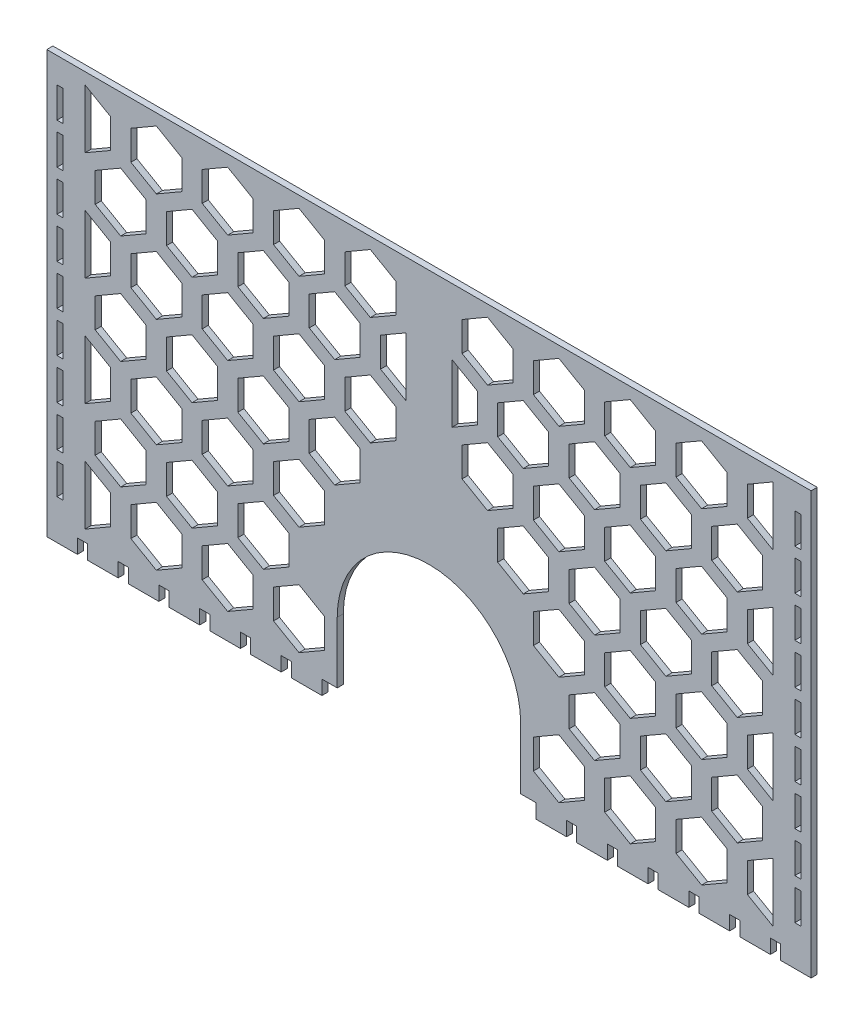
SolidWorks part; units mm, degrees
material "Brass"
ref_plane "Front Plane" through (0, 0, 0) normal (0, 0, 1) x (1, 0, 0)
ref_plane "Top Plane" through (0, 0, 0) normal (0, 1, 0) x (1, 0, 0)
ref_plane "Right Plane" through (0, 0, 0) normal (1, 0, 0) x (0, 0, -1)
sketch "Sketch1" plane through (0, 0, 0) normal (0, 0, 1) x (1, 0, 0)
  line L0 (0, 100) -> (0, -100) construction
  line L2 (-187.5, -100) -> (-187.5, 100)
  line L3 (-187.5, 100) -> (187.5, 100)
  line L4 (187.5, -100) -> (187.5, 100)
  line L6 (-187.5, 0) -> (187.5, 0) construction
  line L11 (-187.5, -100) -> (187.5, -100)
  line L13 (-187.5, 0) -> (-182.5, 0) construction
  line L15 (-45, -70) -> (-45, -100)
  line L16 (-45, -100) -> (45, -100)
  line L17 (45, -70) -> (45, -100)
  line L18 (-179.5, 7.5) -> (-182.5, 7.5)
  line L19 (-179.5, 7.5) -> (-179.5, -7.5)
  line L20 (-179.5, -7.5) -> (-182.5, -7.5)
  line L21 (-182.5, 7.5) -> (-182.5, -7.5)
  line L22 (-179.5, 27.5) -> (-179.5, 12.5)
  line L23 (-179.5, 27.5) -> (-182.5, 27.5)
  line L24 (-182.5, 27.5) -> (-182.5, 12.5)
  line L25 (-179.5, 12.5) -> (-182.5, 12.5)
  line L26 (-179.5, 47.5) -> (-179.5, 32.5)
  line L27 (-179.5, 47.5) -> (-182.5, 47.5)
  line L28 (-182.5, 47.5) -> (-182.5, 32.5)
  line L29 (-179.5, 32.5) -> (-182.5, 32.5)
  line L30 (-179.5, 67.5) -> (-179.5, 52.5)
  line L31 (-179.5, 67.5) -> (-182.5, 67.5)
  line L32 (-182.5, 67.5) -> (-182.5, 52.5)
  line L33 (-179.5, 52.5) -> (-182.5, 52.5)
  line L34 (-179.5, 87.5) -> (-179.5, 72.5)
  line L35 (-179.5, 87.5) -> (-182.5, 87.5)
  line L36 (-182.5, 87.5) -> (-182.5, 72.5)
  line L37 (-179.5, 72.5) -> (-182.5, 72.5)
  line L38 (-179.5, 7.5) -> (-179.5, -7.5)
  line L39 (-179.5, 7.5) -> (-182.5, 7.5)
  line L40 (-182.5, 7.5) -> (-182.5, -7.5)
  line L41 (-179.5, -7.5) -> (-182.5, -7.5)
  line L42 (-179.5, 27.5) -> (-179.5, 12.5)
  line L43 (-179.5, 27.5) -> (-182.5, 27.5)
  line L44 (-182.5, 27.5) -> (-182.5, 12.5)
  line L45 (-179.5, 12.5) -> (-182.5, 12.5)
  line L46 (-179.5, 47.5) -> (-179.5, 32.5)
  line L47 (-179.5, 47.5) -> (-182.5, 47.5)
  line L48 (-182.5, 47.5) -> (-182.5, 32.5)
  line L49 (-179.5, 32.5) -> (-182.5, 32.5)
  line L50 (-179.5, 67.5) -> (-179.5, 52.5)
  line L51 (-179.5, 67.5) -> (-182.5, 67.5)
  line L52 (-182.5, 67.5) -> (-182.5, 52.5)
  line L53 (-179.5, 52.5) -> (-182.5, 52.5)
  line L54 (-179.5, -12.5) -> (-179.5, -27.5)
  line L55 (-179.5, -12.5) -> (-182.5, -12.5)
  line L56 (-182.5, -12.5) -> (-182.5, -27.5)
  line L57 (-179.5, -27.5) -> (-182.5, -27.5)
  line L58 (-179.5, 7.5) -> (-179.5, -7.5)
  line L59 (-179.5, 7.5) -> (-182.5, 7.5)
  line L60 (-182.5, 7.5) -> (-182.5, -7.5)
  line L61 (-179.5, -7.5) -> (-182.5, -7.5)
  line L62 (-179.5, 27.5) -> (-179.5, 12.5)
  line L63 (-179.5, 27.5) -> (-182.5, 27.5)
  line L64 (-182.5, 27.5) -> (-182.5, 12.5)
  line L65 (-179.5, 12.5) -> (-182.5, 12.5)
  line L66 (-179.5, 47.5) -> (-179.5, 32.5)
  line L67 (-179.5, 47.5) -> (-182.5, 47.5)
  line L68 (-182.5, 47.5) -> (-182.5, 32.5)
  line L69 (-179.5, 32.5) -> (-182.5, 32.5)
  line L70 (-179.5, -32.5) -> (-179.5, -47.5)
  line L71 (-179.5, -32.5) -> (-182.5, -32.5)
  line L72 (-182.5, -32.5) -> (-182.5, -47.5)
  line L73 (-179.5, -47.5) -> (-182.5, -47.5)
  line L74 (-179.5, -12.5) -> (-179.5, -27.5)
  line L75 (-179.5, -12.5) -> (-182.5, -12.5)
  line L76 (-182.5, -12.5) -> (-182.5, -27.5)
  line L77 (-179.5, -27.5) -> (-182.5, -27.5)
  line L78 (-179.5, 7.5) -> (-179.5, -7.5)
  line L79 (-179.5, 7.5) -> (-182.5, 7.5)
  line L80 (-182.5, 7.5) -> (-182.5, -7.5)
  line L81 (-179.5, -7.5) -> (-182.5, -7.5)
  line L82 (-179.5, 27.5) -> (-179.5, 12.5)
  line L83 (-179.5, 27.5) -> (-182.5, 27.5)
  line L84 (-182.5, 27.5) -> (-182.5, 12.5)
  line L85 (-179.5, 12.5) -> (-182.5, 12.5)
  line L86 (-179.5, -52.5) -> (-179.5, -67.5)
  line L87 (-179.5, -52.5) -> (-182.5, -52.5)
  line L88 (-182.5, -52.5) -> (-182.5, -67.5)
  line L89 (-179.5, -67.5) -> (-182.5, -67.5)
  line L90 (-179.5, -32.5) -> (-179.5, -47.5)
  line L91 (-179.5, -32.5) -> (-182.5, -32.5)
  line L92 (-182.5, -32.5) -> (-182.5, -47.5)
  line L93 (-179.5, -47.5) -> (-182.5, -47.5)
  line L94 (-179.5, -12.5) -> (-179.5, -27.5)
  line L95 (-179.5, -12.5) -> (-182.5, -12.5)
  line L96 (-182.5, -12.5) -> (-182.5, -27.5)
  line L97 (-179.5, -27.5) -> (-182.5, -27.5)
  line L98 (-179.5, 7.5) -> (-179.5, -7.5)
  line L99 (-179.5, 7.5) -> (-182.5, 7.5)
  line L100 (-182.5, 7.5) -> (-182.5, -7.5)
  line L101 (-179.5, -7.5) -> (-182.5, -7.5)
  line L102 (-179.5, -12.5) -> (-179.5, -27.5)
  line L103 (-179.5, -12.5) -> (-182.5, -12.5)
  line L104 (-182.5, -12.5) -> (-182.5, -27.5)
  line L105 (-179.5, -27.5) -> (-182.5, -27.5)
  line L106 (-179.5, -32.5) -> (-179.5, -47.5)
  line L107 (-179.5, -32.5) -> (-182.5, -32.5)
  line L108 (-182.5, -32.5) -> (-182.5, -47.5)
  line L109 (-179.5, -47.5) -> (-182.5, -47.5)
  line L110 (-179.5, -52.5) -> (-179.5, -67.5)
  line L111 (-179.5, -52.5) -> (-182.5, -52.5)
  line L112 (-182.5, -52.5) -> (-182.5, -67.5)
  line L113 (-179.5, -67.5) -> (-182.5, -67.5)
  line L114 (-179.5, -72.5) -> (-179.5, -87.5)
  line L115 (-179.5, -72.5) -> (-182.5, -72.5)
  line L116 (-182.5, -72.5) -> (-182.5, -87.5)
  line L117 (-179.5, -87.5) -> (-182.5, -87.5)
  line L118 (187.5, 0) -> (182.5, 0) construction
  line L119 (182.5, 27.5) -> (179.5, 27.5)
  line L120 (179.5, 27.5) -> (179.5, 12.5)
  line L121 (182.5, 7.5) -> (179.5, 7.5)
  line L122 (182.5, 7.5) -> (182.5, -7.5)
  line L123 (182.5, -7.5) -> (179.5, -7.5)
  line L124 (179.5, 7.5) -> (179.5, -7.5)
  line L221 (182.5, 12.5) -> (179.5, 12.5)
  line L222 (182.5, 27.5) -> (182.5, 12.5)
  line L223 (182.5, 47.5) -> (179.5, 47.5)
  line L224 (179.5, 47.5) -> (179.5, 32.5)
  line L225 (182.5, 32.5) -> (179.5, 32.5)
  line L226 (182.5, 47.5) -> (182.5, 32.5)
  line L227 (182.5, 67.5) -> (179.5, 67.5)
  line L228 (179.5, 67.5) -> (179.5, 52.5)
  line L229 (182.5, 52.5) -> (179.5, 52.5)
  line L230 (182.5, 67.5) -> (182.5, 52.5)
  line L231 (182.5, 87.5) -> (179.5, 87.5)
  line L232 (179.5, 87.5) -> (179.5, 72.5)
  line L233 (182.5, 72.5) -> (179.5, 72.5)
  line L234 (182.5, 87.5) -> (182.5, 72.5)
  line L235 (182.5, -12.5) -> (179.5, -12.5)
  line L236 (179.5, -12.5) -> (179.5, -27.5)
  line L237 (182.5, -27.5) -> (179.5, -27.5)
  line L238 (182.5, -12.5) -> (182.5, -27.5)
  line L239 (182.5, -32.5) -> (179.5, -32.5)
  line L240 (179.5, -32.5) -> (179.5, -47.5)
  line L241 (182.5, -47.5) -> (179.5, -47.5)
  line L242 (182.5, -32.5) -> (182.5, -47.5)
  line L243 (182.5, -52.5) -> (179.5, -52.5)
  line L244 (179.5, -52.5) -> (179.5, -67.5)
  line L245 (182.5, -67.5) -> (179.5, -67.5)
  line L246 (182.5, -52.5) -> (182.5, -67.5)
  line L247 (182.5, -72.5) -> (179.5, -72.5)
  line L248 (179.5, -72.5) -> (179.5, -87.5)
  line L249 (182.5, -87.5) -> (179.5, -87.5)
  line L250 (182.5, -72.5) -> (182.5, -87.5)
  arc A1 (45, -70) -> (-45, -70) centre (0, -70) ccw
  circle A2 centre (0, -70) radius 40 construction
  point P0 (0, 0)
  point P16 (0, 0)
  point P17 (-182.5, 0)
  point P121 (182.5, 0)
  point P122 (181, 7.5)
  dimension "D3" = 90
  dimension "D5" = 30
  dimension "D4" = 142.5
  dimension "D6" = 80
  dimension "D2" = 187.5
  dimension "D7" = 15
  dimension "D8" = 3
  dimension "D9" = 5
  dimension "D12" = 5
  dimension "D13" = 5
  dimension "D14" = 200
  dimension "D15" = 15
  dimension "D16" = 3
  dimension "D17" = 5
  dimension "D18" = 5
  dimension "D19" = 5
  dimension "D21" = 5
  dimension "D10" = 5
  dimension "D11" = 5
  dimension "D20" = 5
extrude "Boss-Extrude1" add sketch "Sketch1" along normal blind 3 contours A1 L17 L11 L4 L3 L2 L15
sketch "Sketch7" plane through (0, -100, 0) normal (0, -1, 0) x (1, 0, 0)
  line L0 (-187.5, 0) -> (-45, 0) construction
  line L1 (-187.5, 3) -> (-172.5, 3)
  line L2 (-187.5, 3) -> (-187.5, 0)
  line L3 (-187.5, 0) -> (-172.5, 0)
  line L4 (-172.5, 3) -> (-172.5, 0)
  line L5 (-167.5, 3) -> (-167.5, 0)
  line L6 (-167.5, 3) -> (-152.5, 3)
  line L7 (-152.5, 3) -> (-152.5, 0)
  line L8 (-167.5, 0) -> (-152.5, 0)
  line L9 (-147.5, 3) -> (-147.5, 0)
  line L10 (-147.5, 3) -> (-132.5, 3)
  line L11 (-132.5, 3) -> (-132.5, 0)
  line L12 (-147.5, 0) -> (-132.5, 0)
  line L13 (-127.5, 3) -> (-127.5, 0)
  line L14 (-127.5, 3) -> (-112.5, 3)
  line L15 (-112.5, 3) -> (-112.5, 0)
  line L16 (-127.5, 0) -> (-112.5, 0)
  line L17 (-107.5, 3) -> (-107.5, 0)
  line L18 (-107.5, 3) -> (-92.5, 3)
  line L19 (-92.5, 3) -> (-92.5, 0)
  line L20 (-107.5, 0) -> (-92.5, 0)
  line L21 (-87.5, 3) -> (-87.5, 0)
  line L22 (-87.5, 3) -> (-72.5, 3)
  line L23 (-72.5, 3) -> (-72.5, 0)
  line L24 (-87.5, 0) -> (-72.5, 0)
  line L25 (-67.5, 3) -> (-67.5, 0)
  line L26 (-67.5, 3) -> (-52.5, 3)
  line L27 (-52.5, 3) -> (-52.5, 0)
  line L28 (-67.5, 0) -> (-52.5, 0)
  dimension "D1" = 15
  dimension "D3" = 5
  dimension "D2" = 7
extrude "Boss-Extrude2" add sketch "Sketch7" along normal blind 7
sketch "Sketch8" plane through (0, -100, 0) normal (0, -1, 0) x (1, 0, 0)
  line L0 (45, 3) -> (187.5, 3) construction
  line L1 (187.5, 0) -> (172.5, 0)
  line L2 (187.5, 0) -> (187.5, 3)
  line L3 (187.5, 3) -> (172.5, 3)
  line L4 (172.5, 0) -> (172.5, 3)
  line L5 (167.5, 0) -> (167.5, 3)
  line L6 (167.5, 0) -> (152.5, 0)
  line L7 (152.5, 0) -> (152.5, 3)
  line L8 (167.5, 3) -> (152.5, 3)
  line L9 (147.5, 0) -> (147.5, 3)
  line L10 (147.5, 0) -> (132.5, 0)
  line L11 (132.5, 0) -> (132.5, 3)
  line L12 (147.5, 3) -> (132.5, 3)
  line L13 (127.5, 0) -> (127.5, 3)
  line L14 (127.5, 0) -> (112.5, 0)
  line L15 (112.5, 0) -> (112.5, 3)
  line L16 (127.5, 3) -> (112.5, 3)
  line L17 (107.5, 0) -> (107.5, 3)
  line L18 (107.5, 0) -> (92.5, 0)
  line L19 (92.5, 0) -> (92.5, 3)
  line L20 (107.5, 3) -> (92.5, 3)
  line L21 (87.5, 0) -> (87.5, 3)
  line L22 (87.5, 0) -> (72.5, 0)
  line L23 (72.5, 0) -> (72.5, 3)
  line L24 (87.5, 3) -> (72.5, 3)
  line L25 (67.5, 0) -> (67.5, 3)
  line L26 (67.5, 0) -> (52.5, 0)
  line L27 (52.5, 0) -> (52.5, 3)
  line L28 (67.5, 3) -> (52.5, 3)
  dimension "D1" = 15
  dimension "D3" = 5
  dimension "D2" = 7
extrude "Boss-Extrude3" add sketch "Sketch8" along normal blind 7
sketch "Sketch10" plane through (0, 0, 0) normal (0, 0, -1) x (-1, 0, 0)
  line L0 (-45, -100) -> (-45, 100) construction
  line L1 (187.5, 100) -> (-187.5, 100) construction
  line L2 (-45, 100) -> (-187.5, 100) construction
  line L3 (-187.5, 100) -> (-187.5, -100) construction
  line L4 (-187.5, -107) -> (-187.5, 100) construction
  line L5 (-187.5, -100) -> (-45, -100) construction
  line L6 (-116.25, 100) -> (-116.25, -100) construction
  line L7 (-98.75, -26.6506) -> (-98.75, -100) construction
  line L8 (-45, 0) -> (-187.5, 0) construction
  line L9 (-116.25, -14.4338) -> (-103.75, -7.2169)
  line L10 (-103.75, -7.2169) -> (-103.75, 7.2169)
  line L11 (-103.75, 7.2169) -> (-116.25, 14.4338)
  line L12 (-116.25, 14.4338) -> (-128.75, 7.2169)
  line L13 (-128.75, 7.2169) -> (-128.75, -7.2169)
  line L14 (-128.75, -7.2169) -> (-116.25, -14.4338)
  line L15 (-98.75, -100) -> (-98.75, 100) construction
  line L16 (-98.75, -12.2169) -> (-111.25, -19.4338)
  line L17 (-111.25, -19.4338) -> (-111.25, -33.8675)
  line L18 (-111.25, -33.8675) -> (-98.75, -41.0844)
  line L19 (-98.75, -41.0844) -> (-86.25, -33.8675)
  line L20 (-86.25, -33.8675) -> (-86.25, -19.4338)
  line L21 (-86.25, -19.4338) -> (-98.75, -12.2169)
  line L22 (-133.75, -100) -> (-133.75, 100) construction
  line L23 (-45, -26.6506) -> (-187.5, -26.6506) construction
  line L24 (-133.75, -41.0844) -> (-121.25, -33.8675)
  line L25 (-121.25, -33.8675) -> (-121.25, -19.4338)
  line L26 (-121.25, -19.4338) -> (-133.75, -12.2169)
  line L27 (-133.75, -12.2169) -> (-146.25, -19.4338)
  line L28 (-146.25, -19.4338) -> (-146.25, -33.8675)
  line L29 (-146.25, -33.8675) -> (-133.75, -41.0844)
  line L36 (187.5, -107) -> (187.5, 100) construction
  line L37 (-116.25, -67.735) -> (-103.75, -60.5181)
  line L38 (-103.75, -60.5181) -> (-103.75, -46.0844)
  line L39 (-103.75, -46.0844) -> (-116.25, -38.8675)
  line L40 (-116.25, -38.8675) -> (-128.75, -46.0844)
  line L41 (-128.75, -46.0844) -> (-128.75, -60.5181)
  line L42 (-128.75, -60.5181) -> (-116.25, -67.735)
  line L61 (-81.25, -14.4338) -> (-68.75, -7.2169)
  line L62 (-68.75, -7.2169) -> (-68.75, 7.2169)
  line L63 (-68.75, 7.2169) -> (-81.25, 14.4338)
  line L64 (-81.25, 14.4338) -> (-93.75, 7.2169)
  line L65 (-93.75, 7.2169) -> (-93.75, -7.2169)
  line L66 (-93.75, -7.2169) -> (-81.25, -14.4338)
  line L67 (-81.25, -67.735) -> (-68.75, -60.5181)
  line L68 (-68.75, -60.5181) -> (-68.75, -46.0844)
  line L69 (-68.75, -46.0844) -> (-81.25, -38.8675)
  line L70 (-81.25, -38.8675) -> (-93.75, -46.0844)
  line L71 (-93.75, -46.0844) -> (-93.75, -60.5181)
  line L72 (-93.75, -60.5181) -> (-81.25, -67.735)
  line L73 (-63.75, -41.0844) -> (-51.25, -33.8675)
  line L74 (-51.25, -33.8675) -> (-51.25, -19.4338)
  line L75 (-51.25, -19.4338) -> (-63.75, -12.2169)
  line L76 (-63.75, -12.2169) -> (-76.25, -19.4338)
  line L77 (-76.25, -19.4338) -> (-76.25, -33.8675)
  line L78 (-76.25, -33.8675) -> (-63.75, -41.0844)
  line L79 (-151.25, -14.4338) -> (-138.75, -7.2169)
  line L80 (-138.75, -7.2169) -> (-138.75, 7.2169)
  line L81 (-138.75, 7.2169) -> (-151.25, 14.4338)
  line L82 (-151.25, 14.4338) -> (-163.75, 7.2169)
  line L83 (-163.75, 7.2169) -> (-163.75, -7.2169)
  line L84 (-163.75, -7.2169) -> (-151.25, -14.4338)
  line L85 (-151.25, -67.735) -> (-138.75, -60.5181)
  line L86 (-138.75, -60.5181) -> (-138.75, -46.0844)
  line L87 (-138.75, -46.0844) -> (-151.25, -38.8675)
  line L88 (-151.25, -38.8675) -> (-163.75, -46.0844)
  line L89 (-163.75, -46.0844) -> (-163.75, -60.5181)
  line L90 (-163.75, -60.5181) -> (-151.25, -67.735)
  line L91 (-168.75, -41.0844) -> (-156.25, -33.8675)
  line L92 (-156.25, -33.8675) -> (-156.25, -19.4338)
  line L93 (-156.25, -19.4338) -> (-168.75, -12.2169)
  line L96 (-168.75, -12.2169) -> (-168.75, -41.0844)
  line L103 (-133.75, 12.2169) -> (-121.25, 19.4338)
  line L104 (-121.25, 19.4338) -> (-121.25, 33.8675)
  line L105 (-121.25, 33.8675) -> (-133.75, 41.0844)
  line L106 (-133.75, 41.0844) -> (-146.25, 33.8675)
  line L107 (-146.25, 33.8675) -> (-146.25, 19.4338)
  line L108 (-146.25, 19.4338) -> (-133.75, 12.2169)
  line L109 (-98.75, 12.2169) -> (-86.25, 19.4338)
  line L110 (-86.25, 19.4338) -> (-86.25, 33.8675)
  line L111 (-86.25, 33.8675) -> (-98.75, 41.0844)
  line L112 (-98.75, 41.0844) -> (-111.25, 33.8675)
  line L113 (-111.25, 33.8675) -> (-111.25, 19.4338)
  line L114 (-111.25, 19.4338) -> (-98.75, 12.2169)
  line L115 (-168.75, 12.2169) -> (-156.25, 19.4338)
  line L116 (-156.25, 19.4338) -> (-156.25, 33.8675)
  line L117 (-156.25, 33.8675) -> (-168.75, 41.0844)
  line L118 (-168.75, 41.0844) -> (-168.75, 12.2169)
  line L119 (-63.75, 12.2169) -> (-51.25, 19.4338)
  line L120 (-51.25, 19.4338) -> (-51.25, 33.8675)
  line L121 (-51.25, 33.8675) -> (-63.75, 41.0844)
  line L122 (-63.75, 41.0844) -> (-76.25, 33.8675)
  line L123 (-76.25, 33.8675) -> (-76.25, 19.4338)
  line L124 (-76.25, 19.4338) -> (-63.75, 12.2169)
  line L125 (-28.75, 12.2169) -> (-16.25, 19.4338)
  line L126 (-16.25, 19.4338) -> (-16.25, 33.8675)
  line L127 (-16.25, 33.8675) -> (-28.75, 41.0844)
  line L128 (-28.75, 41.0844) -> (-41.25, 33.8675)
  line L129 (-41.25, 33.8675) -> (-41.25, 19.4338)
  line L130 (-41.25, 19.4338) -> (-28.75, 12.2169)
  line L131 (-46.25, -14.4338) -> (-33.75, -7.2169)
  line L132 (-33.75, -7.2169) -> (-33.75, 7.2169)
  line L133 (-33.75, 7.2169) -> (-46.25, 14.4338)
  line L134 (-46.25, 14.4338) -> (-58.75, 7.2169)
  line L135 (-58.75, 7.2169) -> (-58.75, -7.2169)
  line L136 (-58.75, -7.2169) -> (-46.25, -14.4338)
  line L137 (0, -25) -> (0, 100) construction
  line L138 (-133.75, -94.3857) -> (-121.25, -87.1688)
  line L139 (-121.25, -87.1688) -> (-121.25, -72.735)
  line L140 (-121.25, -72.735) -> (-133.75, -65.5181)
  line L141 (-133.75, -65.5181) -> (-146.25, -72.735)
  line L142 (-146.25, -72.735) -> (-146.25, -87.1688)
  line L143 (-146.25, -87.1688) -> (-133.75, -94.3857)
  line L144 (-98.75, -94.3857) -> (-86.25, -87.1688)
  line L145 (-86.25, -87.1688) -> (-86.25, -72.735)
  line L146 (-86.25, -72.735) -> (-98.75, -65.5181)
  line L147 (-98.75, -65.5181) -> (-111.25, -72.735)
  line L148 (-111.25, -72.735) -> (-111.25, -87.1688)
  line L149 (-111.25, -87.1688) -> (-98.75, -94.3857)
  line L150 (-63.75, -94.3857) -> (-51.25, -87.1688)
  line L151 (-51.25, -87.1688) -> (-51.25, -72.735)
  line L152 (-51.25, -72.735) -> (-63.75, -65.5181)
  line L153 (-63.75, -65.5181) -> (-76.25, -72.735)
  line L154 (-76.25, -72.735) -> (-76.25, -87.1688)
  line L155 (-76.25, -87.1688) -> (-63.75, -94.3857)
  line L156 (-168.75, -94.3857) -> (-156.25, -87.1688)
  line L157 (-156.25, -87.1688) -> (-156.25, -72.735)
  line L158 (-156.25, -72.735) -> (-168.75, -65.5181)
  line L159 (-168.75, -65.5181) -> (-168.75, -94.3857)
  line L160 (-151.25, 38.8675) -> (-138.75, 46.0844)
  line L161 (-138.75, 46.0844) -> (-138.75, 60.5181)
  line L162 (-138.75, 60.5181) -> (-151.25, 67.735)
  line L163 (-151.25, 67.735) -> (-163.75, 60.5181)
  line L164 (-163.75, 60.5181) -> (-163.75, 46.0844)
  line L165 (-163.75, 46.0844) -> (-151.25, 38.8675)
  line L166 (-116.25, 38.8675) -> (-103.75, 46.0844)
  line L167 (-103.75, 46.0844) -> (-103.75, 60.5181)
  line L168 (-103.75, 60.5181) -> (-116.25, 67.735)
  line L169 (-116.25, 67.735) -> (-128.75, 60.5181)
  line L170 (-128.75, 60.5181) -> (-128.75, 46.0844)
  line L171 (-128.75, 46.0844) -> (-116.25, 38.8675)
  line L172 (-81.25, 38.8675) -> (-68.75, 46.0844)
  line L173 (-68.75, 46.0844) -> (-68.75, 60.5181)
  line L174 (-68.75, 60.5181) -> (-81.25, 67.735)
  line L175 (-81.25, 67.735) -> (-93.75, 60.5181)
  line L176 (-93.75, 60.5181) -> (-93.75, 46.0844)
  line L177 (-93.75, 46.0844) -> (-81.25, 38.8675)
  line L178 (-46.25, 38.8675) -> (-33.75, 46.0844)
  line L179 (-33.75, 46.0844) -> (-33.75, 60.5181)
  line L180 (-33.75, 60.5181) -> (-46.25, 67.735)
  line L181 (-46.25, 67.735) -> (-58.75, 60.5181)
  line L182 (-58.75, 60.5181) -> (-58.75, 46.0844)
  line L183 (-58.75, 46.0844) -> (-46.25, 38.8675)
  line L187 (-11.25, 67.735) -> (-23.75, 60.5181)
  line L188 (-23.75, 60.5181) -> (-23.75, 46.0844)
  line L189 (-23.75, 46.0844) -> (-11.25, 38.8675)
  line L190 (-11.25, 67.735) -> (-11.25, 38.8675)
  line L191 (-133.75, 65.5181) -> (-121.25, 72.735)
  line L192 (-121.25, 72.735) -> (-121.25, 87.1688)
  line L193 (-121.25, 87.1688) -> (-133.75, 94.3857)
  line L194 (-133.75, 94.3857) -> (-146.25, 87.1688)
  line L195 (-146.25, 87.1688) -> (-146.25, 72.735)
  line L196 (-146.25, 72.735) -> (-133.75, 65.5181)
  line L197 (-98.75, 65.5181) -> (-86.25, 72.735)
  line L198 (-86.25, 72.735) -> (-86.25, 87.1688)
  line L199 (-86.25, 87.1688) -> (-98.75, 94.3857)
  line L200 (-98.75, 94.3857) -> (-111.25, 87.1688)
  line L201 (-111.25, 87.1688) -> (-111.25, 72.735)
  line L202 (-111.25, 72.735) -> (-98.75, 65.5181)
  line L203 (-168.75, 65.5181) -> (-156.25, 72.735)
  line L204 (-156.25, 72.735) -> (-156.25, 87.1688)
  line L205 (-156.25, 87.1688) -> (-168.75, 94.3857)
  line L206 (-168.75, 94.3857) -> (-168.75, 65.5181)
  line L207 (-63.75, 65.5181) -> (-51.25, 72.735)
  line L208 (-51.25, 72.735) -> (-51.25, 87.1688)
  line L209 (-51.25, 87.1688) -> (-63.75, 94.3857)
  line L210 (-63.75, 94.3857) -> (-76.25, 87.1688)
  line L211 (-76.25, 87.1688) -> (-76.25, 72.735)
  line L212 (-76.25, 72.735) -> (-63.75, 65.5181)
  line L213 (-28.75, 65.5181) -> (-16.25, 72.735)
  line L214 (-16.25, 72.735) -> (-16.25, 87.1688)
  line L215 (-16.25, 87.1688) -> (-28.75, 94.3857)
  line L216 (-28.75, 94.3857) -> (-41.25, 87.1688)
  line L217 (-41.25, 87.1688) -> (-41.25, 72.735)
  line L218 (-41.25, 72.735) -> (-28.75, 65.5181)
  line L219 (45, -26.6506) -> (187.5, -26.6506) construction
  line L220 (133.75, -100) -> (133.75, 100) construction
  line L221 (98.75, -100) -> (98.75, 100) construction
  line L222 (45, 0) -> (187.5, 0) construction
  line L223 (98.75, -26.6506) -> (98.75, -100) construction
  line L224 (116.25, 100) -> (116.25, -100) construction
  line L225 (187.5, -100) -> (45, -100) construction
  line L226 (187.5, 100) -> (187.5, -100) construction
  line L227 (45, 100) -> (187.5, 100) construction
  line L228 (45, -100) -> (45, 100) construction
  line L229 (41.25, 72.735) -> (28.75, 65.5181)
  line L230 (41.25, 87.1688) -> (41.25, 72.735)
  line L231 (28.75, 94.3857) -> (41.25, 87.1688)
  line L232 (16.25, 87.1688) -> (28.75, 94.3857)
  line L233 (16.25, 72.735) -> (16.25, 87.1688)
  line L234 (28.75, 65.5181) -> (16.25, 72.735)
  line L235 (76.25, 72.735) -> (63.75, 65.5181)
  line L236 (76.25, 87.1688) -> (76.25, 72.735)
  line L237 (63.75, 94.3857) -> (76.25, 87.1688)
  line L238 (51.25, 87.1688) -> (63.75, 94.3857)
  line L239 (51.25, 72.735) -> (51.25, 87.1688)
  line L240 (63.75, 65.5181) -> (51.25, 72.735)
  line L241 (168.75, 94.3857) -> (168.75, 65.5181)
  line L242 (156.25, 87.1688) -> (168.75, 94.3857)
  line L243 (156.25, 72.735) -> (156.25, 87.1688)
  line L244 (168.75, 65.5181) -> (156.25, 72.735)
  line L245 (111.25, 72.735) -> (98.75, 65.5181)
  line L246 (111.25, 87.1688) -> (111.25, 72.735)
  line L247 (98.75, 94.3857) -> (111.25, 87.1688)
  line L248 (86.25, 87.1688) -> (98.75, 94.3857)
  line L249 (86.25, 72.735) -> (86.25, 87.1688)
  line L250 (98.75, 65.5181) -> (86.25, 72.735)
  line L251 (146.25, 72.735) -> (133.75, 65.5181)
  line L252 (146.25, 87.1688) -> (146.25, 72.735)
  line L253 (133.75, 94.3857) -> (146.25, 87.1688)
  line L254 (121.25, 87.1688) -> (133.75, 94.3857)
  line L255 (121.25, 72.735) -> (121.25, 87.1688)
  line L256 (133.75, 65.5181) -> (121.25, 72.735)
  line L257 (11.25, 67.735) -> (11.25, 38.8675)
  line L258 (23.75, 46.0844) -> (11.25, 38.8675)
  line L259 (23.75, 60.5181) -> (23.75, 46.0844)
  line L260 (11.25, 67.735) -> (23.75, 60.5181)
  line L261 (58.75, 46.0844) -> (46.25, 38.8675)
  line L262 (58.75, 60.5181) -> (58.75, 46.0844)
  line L263 (46.25, 67.735) -> (58.75, 60.5181)
  line L264 (33.75, 60.5181) -> (46.25, 67.735)
  line L265 (33.75, 46.0844) -> (33.75, 60.5181)
  line L266 (46.25, 38.8675) -> (33.75, 46.0844)
  line L267 (93.75, 46.0844) -> (81.25, 38.8675)
  line L268 (93.75, 60.5181) -> (93.75, 46.0844)
  line L269 (81.25, 67.735) -> (93.75, 60.5181)
  line L270 (68.75, 60.5181) -> (81.25, 67.735)
  line L271 (68.75, 46.0844) -> (68.75, 60.5181)
  line L272 (81.25, 38.8675) -> (68.75, 46.0844)
  line L273 (128.75, 46.0844) -> (116.25, 38.8675)
  line L274 (128.75, 60.5181) -> (128.75, 46.0844)
  line L275 (116.25, 67.735) -> (128.75, 60.5181)
  line L276 (103.75, 60.5181) -> (116.25, 67.735)
  line L277 (103.75, 46.0844) -> (103.75, 60.5181)
  line L278 (116.25, 38.8675) -> (103.75, 46.0844)
  line L279 (163.75, 46.0844) -> (151.25, 38.8675)
  line L280 (163.75, 60.5181) -> (163.75, 46.0844)
  line L281 (151.25, 67.735) -> (163.75, 60.5181)
  line L282 (138.75, 60.5181) -> (151.25, 67.735)
  line L283 (138.75, 46.0844) -> (138.75, 60.5181)
  line L284 (151.25, 38.8675) -> (138.75, 46.0844)
  line L285 (168.75, -65.5181) -> (168.75, -94.3857)
  line L286 (156.25, -72.735) -> (168.75, -65.5181)
  line L287 (156.25, -87.1688) -> (156.25, -72.735)
  line L288 (168.75, -94.3857) -> (156.25, -87.1688)
  line L289 (76.25, -87.1688) -> (63.75, -94.3857)
  line L290 (76.25, -72.735) -> (76.25, -87.1688)
  line L291 (63.75, -65.5181) -> (76.25, -72.735)
  line L292 (51.25, -72.735) -> (63.75, -65.5181)
  line L293 (51.25, -87.1688) -> (51.25, -72.735)
  line L294 (63.75, -94.3857) -> (51.25, -87.1688)
  line L295 (111.25, -87.1688) -> (98.75, -94.3857)
  line L296 (111.25, -72.735) -> (111.25, -87.1688)
  line L297 (98.75, -65.5181) -> (111.25, -72.735)
  line L298 (86.25, -72.735) -> (98.75, -65.5181)
  line L299 (86.25, -87.1688) -> (86.25, -72.735)
  line L300 (98.75, -94.3857) -> (86.25, -87.1688)
  line L301 (146.25, -87.1688) -> (133.75, -94.3857)
  line L302 (146.25, -72.735) -> (146.25, -87.1688)
  line L303 (133.75, -65.5181) -> (146.25, -72.735)
  line L304 (121.25, -72.735) -> (133.75, -65.5181)
  line L305 (121.25, -87.1688) -> (121.25, -72.735)
  line L306 (133.75, -94.3857) -> (121.25, -87.1688)
  line L307 (58.75, -7.2169) -> (46.25, -14.4338)
  line L308 (58.75, 7.2169) -> (58.75, -7.2169)
  line L309 (46.25, 14.4338) -> (58.75, 7.2169)
  line L310 (33.75, 7.2169) -> (46.25, 14.4338)
  line L311 (33.75, -7.2169) -> (33.75, 7.2169)
  line L312 (46.25, -14.4338) -> (33.75, -7.2169)
  line L313 (41.25, 19.4338) -> (28.75, 12.2169)
  line L314 (41.25, 33.8675) -> (41.25, 19.4338)
  line L315 (28.75, 41.0844) -> (41.25, 33.8675)
  line L316 (16.25, 33.8675) -> (28.75, 41.0844)
  line L317 (16.25, 19.4338) -> (16.25, 33.8675)
  line L318 (28.75, 12.2169) -> (16.25, 19.4338)
  line L319 (76.25, 19.4338) -> (63.75, 12.2169)
  line L320 (76.25, 33.8675) -> (76.25, 19.4338)
  line L321 (63.75, 41.0844) -> (76.25, 33.8675)
  line L322 (51.25, 33.8675) -> (63.75, 41.0844)
  line L323 (51.25, 19.4338) -> (51.25, 33.8675)
  line L324 (63.75, 12.2169) -> (51.25, 19.4338)
  line L325 (168.75, 41.0844) -> (168.75, 12.2169)
  line L326 (156.25, 33.8675) -> (168.75, 41.0844)
  line L327 (156.25, 19.4338) -> (156.25, 33.8675)
  line L328 (168.75, 12.2169) -> (156.25, 19.4338)
  line L329 (111.25, 19.4338) -> (98.75, 12.2169)
  line L330 (111.25, 33.8675) -> (111.25, 19.4338)
  line L331 (98.75, 41.0844) -> (111.25, 33.8675)
  line L332 (86.25, 33.8675) -> (98.75, 41.0844)
  line L333 (86.25, 19.4338) -> (86.25, 33.8675)
  line L334 (98.75, 12.2169) -> (86.25, 19.4338)
  line L335 (146.25, 19.4338) -> (133.75, 12.2169)
  line L336 (146.25, 33.8675) -> (146.25, 19.4338)
  line L337 (133.75, 41.0844) -> (146.25, 33.8675)
  line L338 (121.25, 33.8675) -> (133.75, 41.0844)
  line L339 (121.25, 19.4338) -> (121.25, 33.8675)
  line L340 (133.75, 12.2169) -> (121.25, 19.4338)
  line L341 (168.75, -12.2169) -> (168.75, -41.0844)
  line L342 (156.25, -19.4338) -> (168.75, -12.2169)
  line L343 (156.25, -33.8675) -> (156.25, -19.4338)
  line L344 (168.75, -41.0844) -> (156.25, -33.8675)
  line L345 (163.75, -60.5181) -> (151.25, -67.735)
  line L346 (163.75, -46.0844) -> (163.75, -60.5181)
  line L347 (151.25, -38.8675) -> (163.75, -46.0844)
  line L348 (138.75, -46.0844) -> (151.25, -38.8675)
  line L349 (138.75, -60.5181) -> (138.75, -46.0844)
  line L350 (151.25, -67.735) -> (138.75, -60.5181)
  line L351 (163.75, -7.2169) -> (151.25, -14.4338)
  line L352 (163.75, 7.2169) -> (163.75, -7.2169)
  line L353 (151.25, 14.4338) -> (163.75, 7.2169)
  line L354 (138.75, 7.2169) -> (151.25, 14.4338)
  line L355 (138.75, -7.2169) -> (138.75, 7.2169)
  line L356 (151.25, -14.4338) -> (138.75, -7.2169)
  line L357 (76.25, -33.8675) -> (63.75, -41.0844)
  line L358 (76.25, -19.4338) -> (76.25, -33.8675)
  line L359 (63.75, -12.2169) -> (76.25, -19.4338)
  line L360 (51.25, -19.4338) -> (63.75, -12.2169)
  line L361 (51.25, -33.8675) -> (51.25, -19.4338)
  line L362 (63.75, -41.0844) -> (51.25, -33.8675)
  line L363 (93.75, -60.5181) -> (81.25, -67.735)
  line L364 (93.75, -46.0844) -> (93.75, -60.5181)
  line L365 (81.25, -38.8675) -> (93.75, -46.0844)
  line L366 (68.75, -46.0844) -> (81.25, -38.8675)
  line L367 (68.75, -60.5181) -> (68.75, -46.0844)
  line L368 (81.25, -67.735) -> (68.75, -60.5181)
  line L369 (93.75, -7.2169) -> (81.25, -14.4338)
  line L370 (93.75, 7.2169) -> (93.75, -7.2169)
  line L371 (81.25, 14.4338) -> (93.75, 7.2169)
  line L372 (68.75, 7.2169) -> (81.25, 14.4338)
  line L373 (68.75, -7.2169) -> (68.75, 7.2169)
  line L374 (81.25, -14.4338) -> (68.75, -7.2169)
  line L375 (128.75, -60.5181) -> (116.25, -67.735)
  line L376 (128.75, -46.0844) -> (128.75, -60.5181)
  line L377 (116.25, -38.8675) -> (128.75, -46.0844)
  line L378 (103.75, -46.0844) -> (116.25, -38.8675)
  line L379 (103.75, -60.5181) -> (103.75, -46.0844)
  line L380 (116.25, -67.735) -> (103.75, -60.5181)
  line L381 (146.25, -33.8675) -> (133.75, -41.0844)
  line L382 (146.25, -19.4338) -> (146.25, -33.8675)
  line L383 (133.75, -12.2169) -> (146.25, -19.4338)
  line L384 (121.25, -19.4338) -> (133.75, -12.2169)
  line L385 (121.25, -33.8675) -> (121.25, -19.4338)
  line L386 (133.75, -41.0844) -> (121.25, -33.8675)
  line L387 (86.25, -19.4338) -> (98.75, -12.2169)
  line L388 (86.25, -33.8675) -> (86.25, -19.4338)
  line L389 (98.75, -41.0844) -> (86.25, -33.8675)
  line L390 (111.25, -33.8675) -> (98.75, -41.0844)
  line L391 (111.25, -19.4338) -> (111.25, -33.8675)
  line L392 (98.75, -12.2169) -> (111.25, -19.4338)
  line L393 (128.75, -7.2169) -> (116.25, -14.4338)
  line L394 (128.75, 7.2169) -> (128.75, -7.2169)
  line L395 (116.25, 14.4338) -> (128.75, 7.2169)
  line L396 (103.75, 7.2169) -> (116.25, 14.4338)
  line L397 (103.75, -7.2169) -> (103.75, 7.2169)
  line L398 (116.25, -14.4338) -> (103.75, -7.2169)
  circle A0 centre (-116.25, 0) radius 12.5 construction
  circle A1 centre (-98.75, -26.6506) radius 12.5 construction
  circle A2 centre (-133.75, -26.6506) radius 12.5 construction
  circle A3 centre (-116.25, -53.3013) radius 12.5 construction
  circle A7 centre (-81.25, 0) radius 12.5 construction
  circle A8 centre (-81.25, -53.3013) radius 12.5 construction
  circle A9 centre (-63.75, -26.6506) radius 12.5 construction
  circle A10 centre (-151.25, 0) radius 12.5 construction
  circle A11 centre (-151.25, -53.3013) radius 12.5 construction
  arc A12 (-162.5, -37.476) -> (-162.5, -15.8253) centre (-168.75, -26.6506) ccw construction
  circle A14 centre (-133.75, 26.6506) radius 12.5 construction
  circle A15 centre (-98.75, 26.6506) radius 12.5 construction
  arc A16 (-162.5, 15.8253) -> (-162.5, 37.476) centre (-168.75, 26.6506) ccw construction
  circle A17 centre (-63.75, 26.6506) radius 12.5 construction
  circle A18 centre (-28.75, 26.6506) radius 12.5 construction
  circle A19 centre (-46.25, 0) radius 12.5 construction
  arc A20 (45, -70) -> (-45, -70) centre (0, -70) ccw construction
  circle A21 centre (-133.75, -79.9519) radius 12.5 construction
  circle A22 centre (-98.75, -79.9519) radius 12.5 construction
  circle A23 centre (-63.75, -79.9519) radius 12.5 construction
  arc A24 (-162.5, -90.7772) -> (-162.5, -69.1266) centre (-168.75, -79.9519) ccw construction
  circle A25 centre (-151.25, 53.3013) radius 12.5 construction
  circle A26 centre (-116.25, 53.3013) radius 12.5 construction
  circle A27 centre (-81.25, 53.3013) radius 12.5 construction
  circle A28 centre (-46.25, 53.3013) radius 12.5 construction
  arc A29 (-17.5, 64.1266) -> (-17.5, 42.476) centre (-11.25, 53.3013) ccw construction
  circle A30 centre (-133.75, 79.9519) radius 12.5 construction
  circle A31 centre (-98.75, 79.9519) radius 12.5 construction
  arc A32 (-162.5, 69.1266) -> (-162.5, 90.7772) centre (-168.75, 79.9519) ccw construction
  circle A33 centre (-63.75, 79.9519) radius 12.5 construction
  circle A34 centre (-28.75, 79.9519) radius 12.5 construction
  circle A35 centre (28.75, 79.9519) radius 12.5 construction
  circle A36 centre (63.75, 79.9519) radius 12.5 construction
  arc A37 (162.5, 69.1266) -> (162.5, 90.7772) centre (168.75, 79.9519) cw construction
  circle A38 centre (98.75, 79.9519) radius 12.5 construction
  circle A39 centre (133.75, 79.9519) radius 12.5 construction
  arc A40 (17.5, 64.1266) -> (17.5, 42.476) centre (11.25, 53.3013) cw construction
  circle A41 centre (46.25, 53.3013) radius 12.5 construction
  circle A42 centre (81.25, 53.3013) radius 12.5 construction
  circle A43 centre (116.25, 53.3013) radius 12.5 construction
  circle A44 centre (151.25, 53.3013) radius 12.5 construction
  arc A45 (162.5, -90.7772) -> (162.5, -69.1266) centre (168.75, -79.9519) cw construction
  circle A46 centre (63.75, -79.9519) radius 12.5 construction
  circle A47 centre (98.75, -79.9519) radius 12.5 construction
  circle A48 centre (133.75, -79.9519) radius 12.5 construction
  circle A49 centre (46.25, 0) radius 12.5 construction
  circle A50 centre (28.75, 26.6506) radius 12.5 construction
  circle A51 centre (63.75, 26.6506) radius 12.5 construction
  arc A52 (162.5, 15.8253) -> (162.5, 37.476) centre (168.75, 26.6506) cw construction
  circle A53 centre (98.75, 26.6506) radius 12.5 construction
  circle A54 centre (133.75, 26.6506) radius 12.5 construction
  arc A55 (162.5, -37.476) -> (162.5, -15.8253) centre (168.75, -26.6506) cw construction
  circle A56 centre (151.25, -53.3013) radius 12.5 construction
  circle A57 centre (151.25, 0) radius 12.5 construction
  circle A58 centre (63.75, -26.6506) radius 12.5 construction
  circle A59 centre (81.25, -53.3013) radius 12.5 construction
  circle A60 centre (81.25, 0) radius 12.5 construction
  circle A61 centre (116.25, -53.3013) radius 12.5 construction
  circle A62 centre (133.75, -26.6506) radius 12.5 construction
  circle A63 centre (98.75, -26.6506) radius 12.5 construction
  circle A64 centre (116.25, 0) radius 12.5 construction
  dimension "D1" = 25
  dimension "D2" = 25
  dimension "D5" = 25
  dimension "D9" = 25
  dimension "D10" = 25
  dimension "D11" = 35
  dimension "D12" = 25
  dimension "D13" = 5
  dimension "D19" = 25
  dimension "D20" = 25
  dimension "D23" = 12.5
  dimension "D24" = 25
  dimension "D25" = 25
  dimension "D27" = 25
  dimension "D28" = 25
  dimension "D30" = 25
  dimension "D32" = 25
  dimension "D34" = 25
  dimension "D35" = 25
  dimension "D36" = 12.5
  dimension "D38" = 25
  dimension "D39" = 25
  dimension "D40" = 25
  dimension "D41" = 25
  dimension "D44" = 25
  dimension "D45" = 5
  dimension "D47" = 12.5
  dimension "D48" = 25
  dimension "D49" = 25
  dimension "D50" = 25
  dimension "D51" = 25
  dimension "D3" = 5
  dimension "D4" = 5
  dimension "D6" = 5
  dimension "D7" = 5
  dimension "D8" = 5
  dimension "D14" = 5
  dimension "D15" = 5
  dimension "D16" = 5
  dimension "D17" = 35
  dimension "D18" = 5
  dimension "D21" = 5
  dimension "D22" = 5
  dimension "D26" = 5
  dimension "D29" = 35
  dimension "D31" = 35
  dimension "D33" = 5
  dimension "D37" = 5
  dimension "D42" = 5
  dimension "D43" = 5
  dimension "D46" = 35
  dimension "D52" = 5
extrude "Cut-Extrude1" cut sketch "Sketch10" against normal through all
